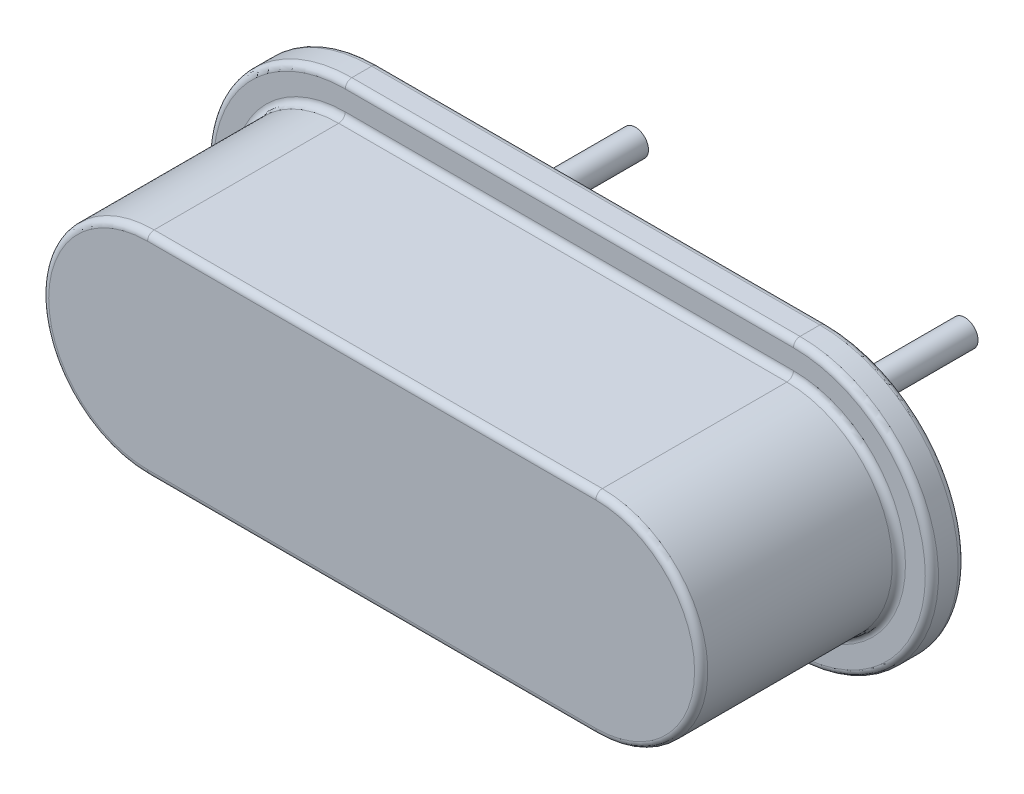
SolidWorks part; units mm, degrees
ref_plane "前视基准面" through (0, 0, 0) normal (0, 0, 1) x (1, 0, 0)
ref_plane "上视基准面" through (0, 0, 0) normal (0, 1, 0) x (1, 0, 0)
ref_plane "右视基准面" through (0, 0, 0) normal (1, 0, 0) x (0, 0, -1)
sketch "草图1" plane through (0, 0, 0) normal (0, 0, 1) x (1, 0, 0)
  line L0 (-1000, 0) -> (49000, 0) construction
  line L1 (0, -1000) -> (0, 49000) construction
  line L2 (3.4, 2.1) -> (-3.4, 2.1)
  line L3 (3.4, -2.1) -> (-3.4, -2.1)
  arc A0 (3.4, -2.1) -> (3.4, 2.1) centre (3.4, 0) ccw
  arc A1 (-3.4, -2.1) -> (-3.4, 2.1) centre (-3.4, 0) cw
  point P10 (0, 2.1)
  point P13 (0, -2.1)
  dimension "D1" = 4.2
  dimension "D2" = 6.8
extrude "凸台-拉伸1" add sketch "草图1" along normal blind 0.5
sketch "草图2" plane through (0, 0, 0.5) normal (0, 0, 1) x (1, 0, 0)
  line L0 (-1000, 0) -> (49000, 0) construction
  line L1 (0, -1000) -> (0, 49000) construction
  line L2 (-3.4, 1.6) -> (3.4, 1.6)
  line L3 (-3.4, -1.6) -> (3.4, -1.6)
  arc A0 (3.4, -1.6) -> (3.4, 1.6) centre (3.4, 0) ccw
  arc A1 (-3.4, -1.6) -> (-3.4, 1.6) centre (-3.4, 0) cw
  point P10 (0, -1.6)
  point P13 (0, 1.6)
  dimension "D2" = 6.8
  dimension "D3" = 3.2
  dimension "D1" = 3.2
extrude "凸台-拉伸2" add sketch "草图2" along normal blind 3
sketch "草图3" plane through (0, 0, 0) normal (0, 0, -1) x (-1, 0, 0)
  line L0 (-1000, 0) -> (49000, 0) construction
  line L1 (0, -1000) -> (0, 49000) construction
  circle A0 centre (-2.5, 0) radius 0.2
  circle A1 centre (2.5, 0) radius 0.2
  dimension "D1" = 0.4
  dimension "D2" = 2.5
extrude "凸台-拉伸3" add sketch "草图3" along normal blind 3
fillet "圆角1" radius 0.1 16 edges at (-5.5, 0, 0) (0, 2.1, 0) (5.5, 0, 0) (-5.5, 0, 0.5) (0, 2.1, 0.5) (5.5, 0, 0.5) (-5, 0, 0.5) (0, 1.6, 0.5) (5, 0, 0.5) (0, 1.6, 3.5) (5, 0, 3.5) (0, -2.1, 0) (0, -2.1, 0.5) (0, -1.6, 0.5) (-5, 0, 3.5) (0, -1.6, 3.5)
